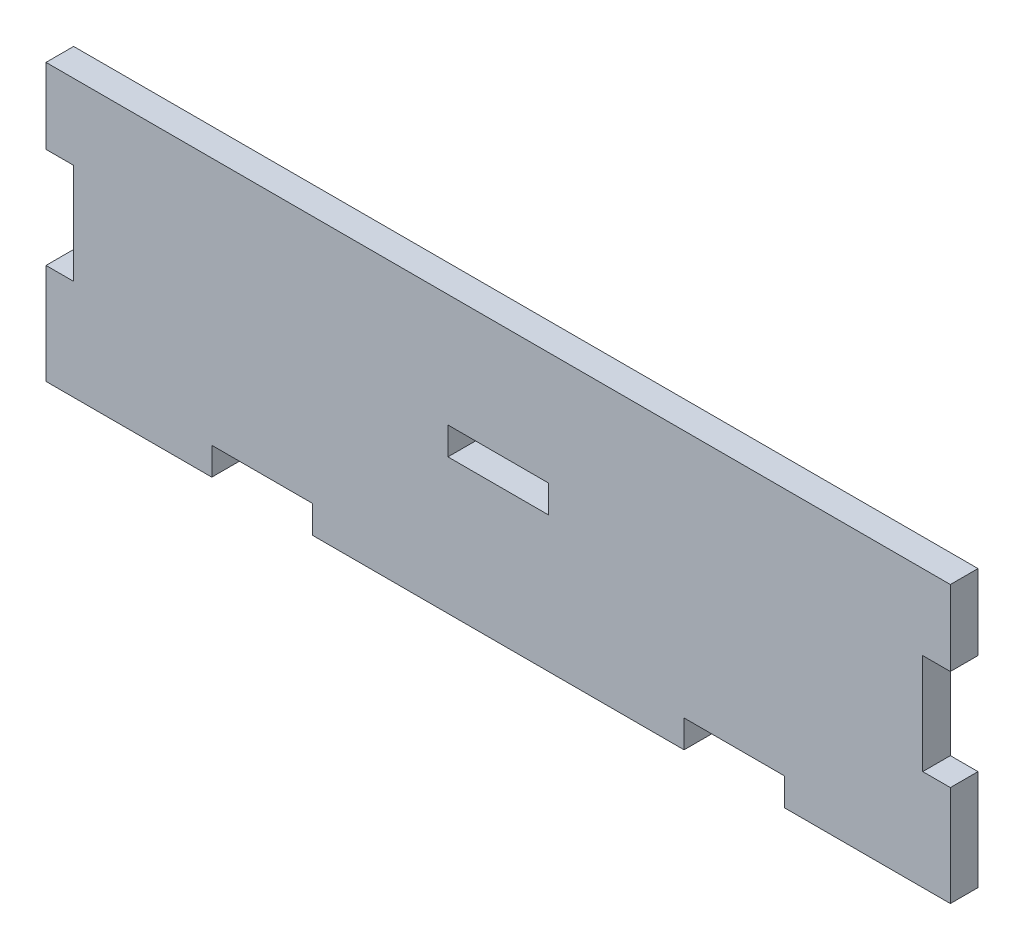
SolidWorks part; units mm, degrees
ref_plane "Front Plane" through (0, 0, 0) normal (0, 0, 1) x (1, 0, 0)
ref_plane "Top Plane" through (0, 0, 0) normal (0, 1, 0) x (1, 0, 0)
ref_plane "Right Plane" through (0, 0, 0) normal (1, 0, 0) x (0, 0, -1)
sketch "Sketch1" plane through (0, 0, 0) normal (0, 0, 1) x (1, 0, 0)
  line L1 (0, 0) -> (33, 0)
  line L2 (0, 0) -> (0, 20)
  line L3 (0, 55) -> (180, 55)
  line L4 (180, 0) -> (180, 20)
  line L5 (174.5, 20) -> (174.5, 40)
  line L6 (33, 5.5) -> (53, 5.5)
  line L7 (5.5, 20) -> (5.5, 40)
  line L8 (90, 55) -> (90, 5) construction
  line L9 (33, 5.5) -> (33, 0)
  line L10 (0, 30) -> (90, 30) construction
  line L11 (0, 40) -> (5.5, 40)
  line L12 (53, 5.5) -> (53, 0)
  line L13 (53, 0) -> (127, 0)
  line L14 (0, 20) -> (5.5, 20)
  line L15 (0, 0) -> (180, 0) construction
  line L16 (174.5, 40) -> (180, 40)
  line L17 (5.5, 5.5) -> (174.5, 5.5) construction
  line L18 (174.5, 20) -> (180, 20)
  line L19 (5.5, 5.5) -> (5.5, 49.5) construction
  line L20 (5.5, 49.5) -> (174.5, 49.5) construction
  line L21 (174.5, 5.5) -> (174.5, 49.5) construction
  line L22 (180, 40) -> (180, 55)
  line L23 (180, 0) -> (180, 55) construction
  line L24 (0, 40) -> (0, 55)
  line L25 (0, 0) -> (0, 55) construction
  line L26 (127, 5.5) -> (127, 0)
  line L27 (147, 5.5) -> (147, 0)
  line L28 (147, 5.5) -> (127, 5.5)
  line L29 (147, 0) -> (180, 0)
  point P27 (90, 30)
  dimension "D1" = 180
  dimension "D2" = 55
  dimension "D4" = 20
  dimension "D5" = 27.5
  dimension "D6" = 20
  dimension "D7" = 10
  dimension "D8" = 20
  dimension "D9" = 10
  dimension "D3" = 5.5
extrude "Boss-Extrude1" add sketch "Sketch1" along normal blind 5.5
sketch "Sketch3" plane through (0, 0, 5.5) normal (0, 0, 1) x (1, 0, 0)
  line L0 (180, 55) -> (0, 55) construction
  line L1 (80, 32.5) -> (100, 32.5)
  line L2 (80, 32.5) -> (80, 27)
  line L3 (80, 27) -> (100, 27)
  line L4 (100, 32.5) -> (100, 27)
  line L5 (90, 55) -> (90, 0) construction
  line L7 (53, 0) -> (127, 0) construction
  dimension "D1" = 20
  dimension "D2" = 22.5
  dimension "D3" = 5.5
extrude "Cut-Extrude2" cut sketch "Sketch3" against normal blind 5.5
